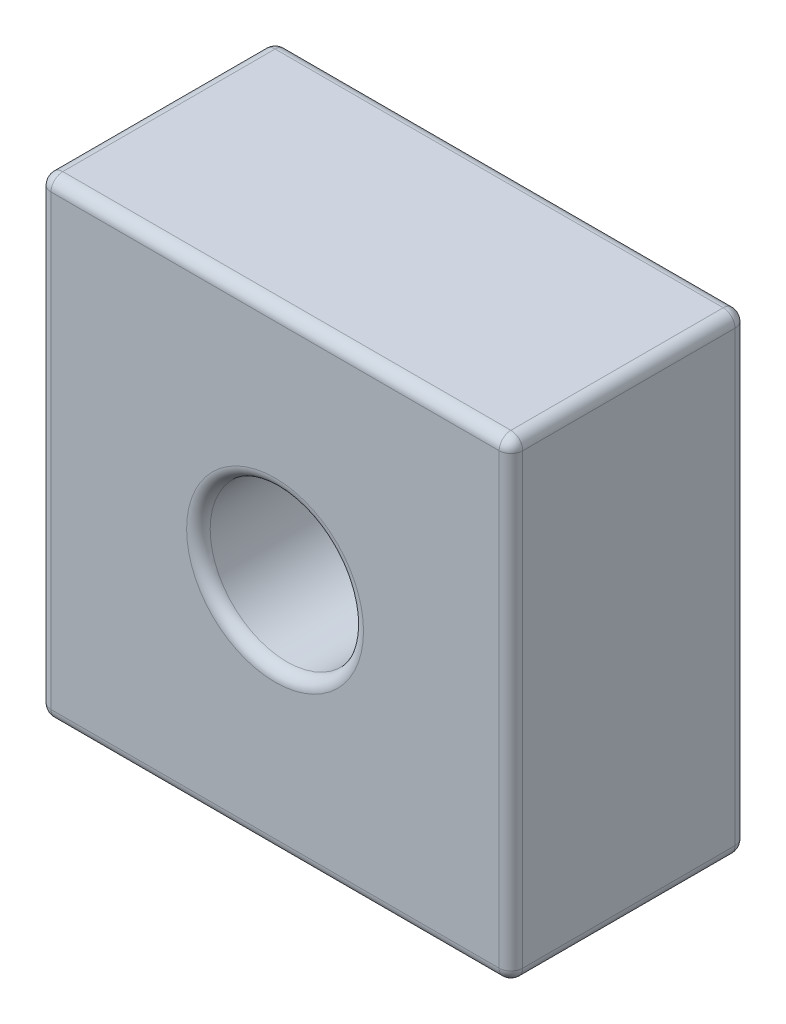
SolidWorks part; units mm, degrees
ref_plane "Plan de face" through (0, 0, 0) normal (0, 0, 1) x (1, 0, 0)
ref_plane "Plan de dessus" through (0, 0, 0) normal (0, 1, 0) x (1, 0, 0)
ref_plane "Plan de droite" through (0, 0, 0) normal (1, 0, 0) x (0, 0, -1)
sketch "Esquisse1" plane through (0, 0, 0) normal (0, 0, 1) x (1, 0, 0)
  line L1 (10, -10) -> (-10, -10)
  line L2 (10, -10) -> (10, 10)
  line L3 (10, 10) -> (-10, 10)
  line L4 (-10, -10) -> (-10, 10)
  line L5 (10, -10) -> (-10, 10) construction
  line L6 (10, 10) -> (-10, -10) construction
  circle A0 centre (0, 0) radius 3.25
  point P0 (0, 0)
  dimension "D3" = 6.5
  dimension "D1" = 20
  dimension "D2" = 20
extrude "Boss.-Extru.1" add sketch "Esquisse1" along normal blind 10
fillet "Congé1" radius 0.5 14 edges at (3.25, 0, 0) (3.25, 0, 10) (-10, 0, 0) (0, -10, 0) (10, 0, 0) (0, 10, 0) (-10, 0, 10) (0, -10, 10) (-10, 10, 5) (10, -10, 5) (-10, -10, 5) (0, 10, 10) (10, 0, 10) (10, 10, 5)
